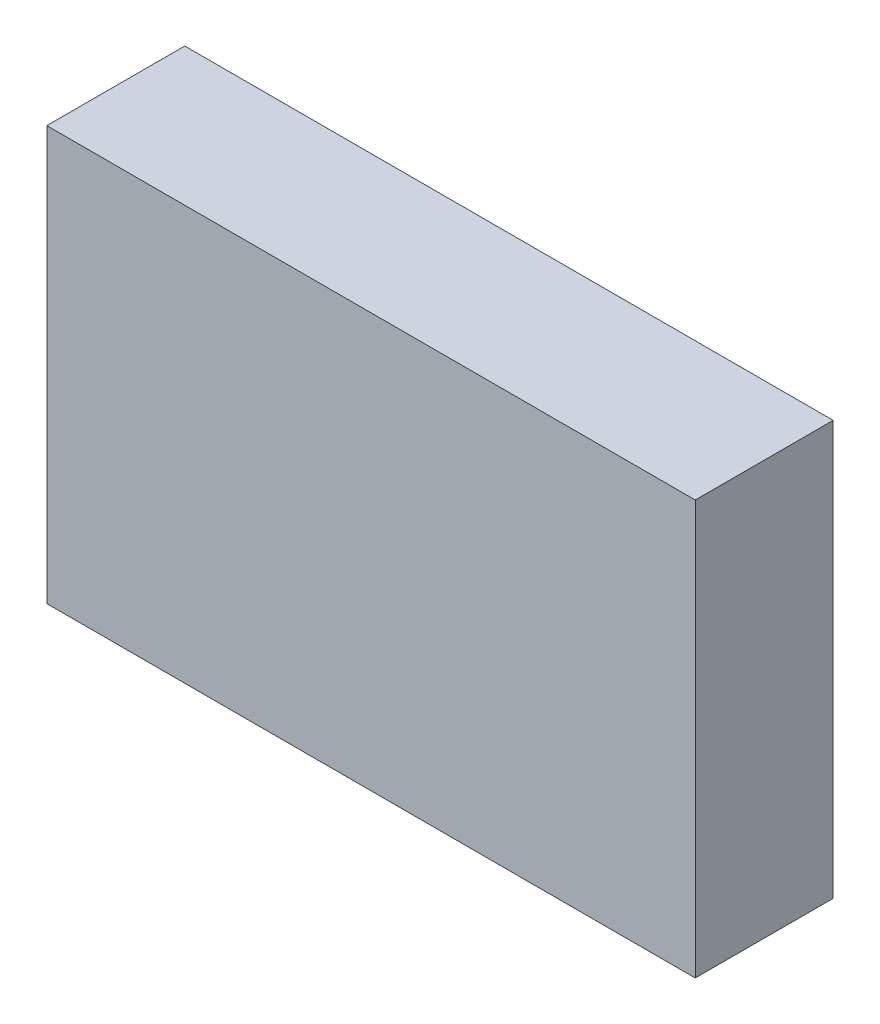
SolidWorks part; units mm, degrees
ref_plane "Front Plane" through (0, 0, 0) normal (0, 0, 1) x (1, 0, 0)
ref_plane "Top Plane" through (0, 0, 0) normal (0, 1, 0) x (1, 0, 0)
ref_plane "Right Plane" through (0, 0, 0) normal (1, 0, 0) x (0, 0, -1)
sketch "Sketch1" plane through (0, 0, 0) normal (0, 0, 1) x (1, 0, 0)
  line L0 (-2.4016, 1.5516) -> (2.3, 1.5516)
  line L1 (2.3, 1.5516) -> (2.3, -1.45)
  line L2 (2.3, -1.45) -> (-2.4016, -1.45)
  line L3 (-2.4016, -1.45) -> (-2.4016, 1.5516)
extrude "Component_Outline" add sketch "Sketch1" along normal blind 1 separate body
sketch3d "3DSketch1"
  line L0 (0, 0, 0) -> (1, 0, 0)
  line L1 (0, 0, 0) -> (0, 1, 0)
  line L2 (0, 0, 0) -> (0, 0, 1)
  point P0 (0, 0, 0)
